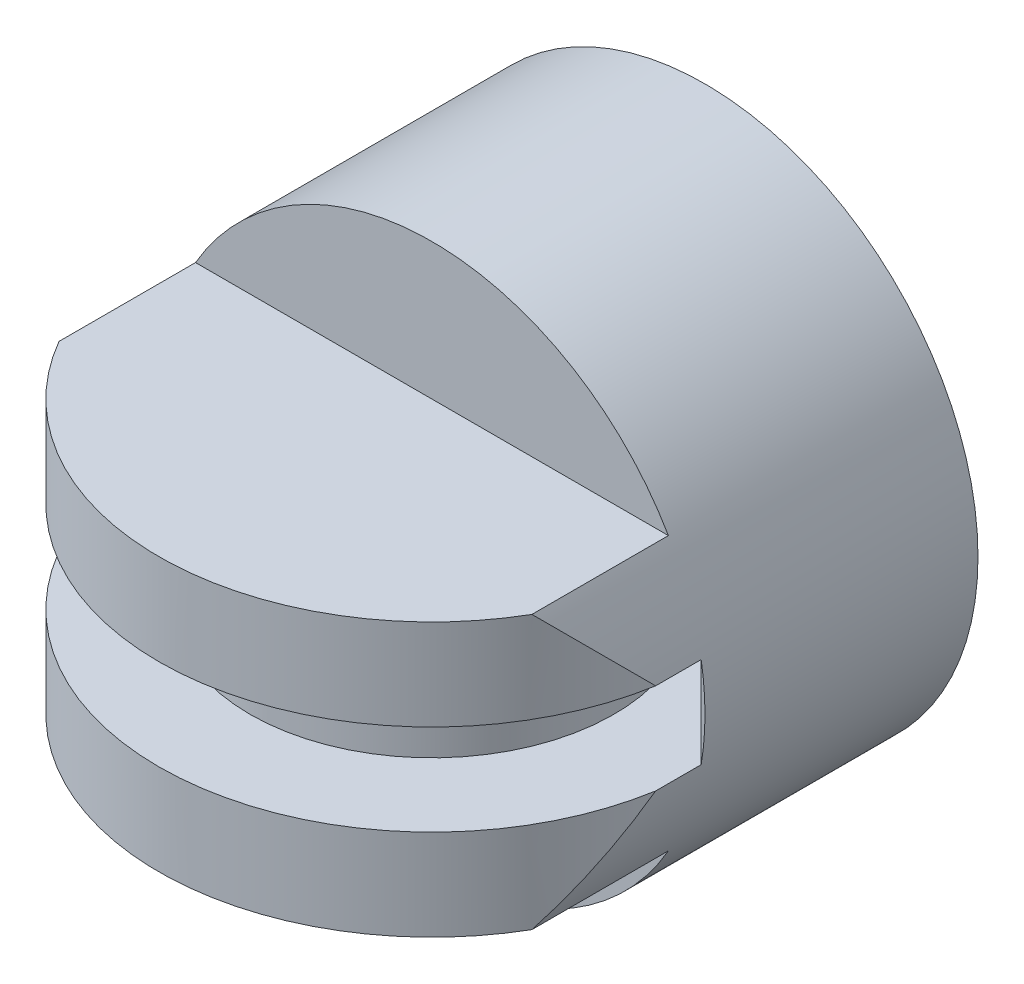
SolidWorks part; units mm, degrees
ref_plane "Front Plane" through (0, 0, 0) normal (0, 0, 1) x (1, 0, 0)
ref_plane "Top Plane" through (0, 0, 0) normal (0, 1, 0) x (1, 0, 0)
ref_plane "Right Plane" through (0, 0, 0) normal (1, 0, 0) x (0, 0, -1)
sketch "Sketch1" plane through (0, 0, 0) normal (0, 1, 0) x (1, 0, 0)
  circle A0 centre (0, 0) radius 20
extrude "Boss-Extrude1" add sketch "Sketch1" along normal blind 10
sketch "Sketch2" plane through (0, 10, 0) normal (0, 1, 0) x (1, 0, 0)
  circle A0 centre (0, 0) radius 30
extrude "Boss-Extrude2" add sketch "Sketch2" along normal blind 10
sketch "Sketch3" plane through (0, 0, 0) normal (0, -1, 0) x (1, 0, 0)
  circle A0 centre (0, 0) radius 30
extrude "Boss-Extrude3" add sketch "Sketch3" along normal blind 10
sketch "Sketch9" plane through (0, 0, 0) normal (0, 0, 1) x (1, 0, 0)
  circle A0 centre (0, 5) radius 30
extrude "Boss-Extrude7" add sketch "Sketch9" against normal blind 30
sketch "Sketch13" plane through (0, 0, 0) normal (0, 0, 1) x (1, 0, 0)
  line L1 (0, 0) -> (0, 5) construction
  circle A1 centre (0, 5) radius 30
  circle A2 centre (0, 5) radius 36.1788
extrude "Cut-Extrude1" cut sketch "Sketch13" against normal through all both and the other way through all
sketch "Sketch14" plane through (0, 0, 0) normal (0, 0, 1) x (1, 0, 0)
  line L0 (0, 0) -> (0, 5) construction
  line L1 (-20, 10) -> (-29.5804, 10)
  line L2 (-29.5804, 10) -> (29.5804, 10) construction
  line L3 (-29.5804, 10) -> (-20, 10) construction
  line L4 (-20, 10) -> (-20, 0)
  line L5 (-20, 0) -> (-29.5804, 0)
  line L6 (29.5804, 10) -> (20, 10)
  line L7 (20, 10) -> (20, 0)
  line L8 (29.5804, 0) -> (-29.5804, 0) construction
  line L9 (29.5804, 0) -> (20, 0) construction
  line L10 (20, 0) -> (29.5804, 0)
  line L11 (29.5804, 10) -> (29.5804, 0)
  arc A1 (29.5804, 0) -> (29.5804, 10) centre (0, 5) ccw
revolve "Cut-Revolve6" cut sketch "Sketch14" angle 180 about L0
